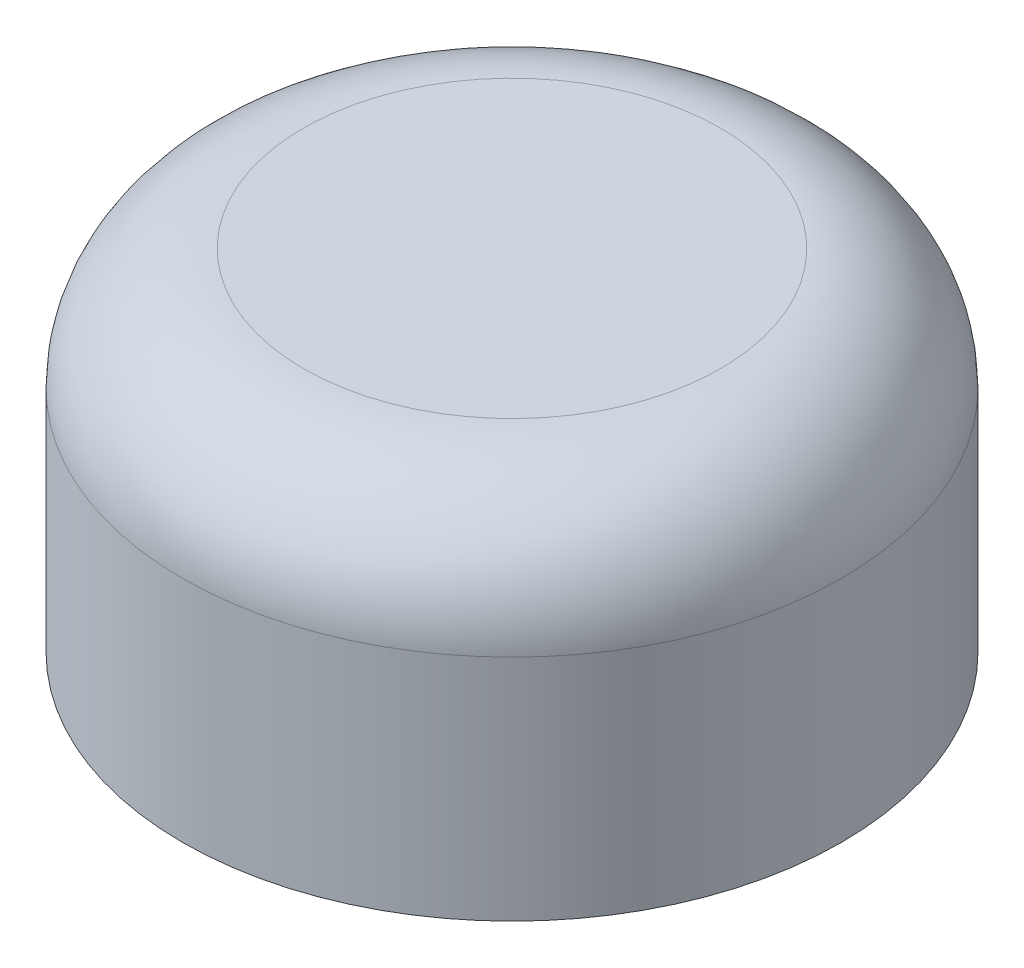
SolidWorks part; units mm, degrees
material "PW30:30:Sc:0:"
ref_plane "Front" through (0, 0, 0) normal (0, 0, 1) x (1, 0, 0)
ref_plane "Top" through (0, 0, 0) normal (0, 1, 0) x (1, 0, 0)
ref_plane "Right" through (0, 0, 0) normal (1, 0, 0) x (0, 0, -1)
sketch "Sketch1" plane through (0, 0, 0) normal (0, 0, 1) x (1, 0, 0)
  line L0 (0, 0) -> (0, 28.1396) construction
  line L1 (0, 22.6983) -> (12.446, 22.6983)
  line L2 (12.446, 22.6983) -> (12.446, 9.4903)
  line L3 (12.446, 9.4903) -> (10.16, 9.4903)
  line L5 (10.16, 9.4903) -> (10.16, 10.7603)
  line L6 (10.16, 10.7603) -> (11.684, 10.7603)
  line L7 (11.684, 10.7603) -> (11.684, 21.4283)
  line L8 (11.684, 21.4283) -> (0, 21.4283)
  line L9 (0, 21.4283) -> (0, 22.6983)
  dimension "D1" = 1.27
  dimension "D2" = 12.446
  dimension "D3" = 0.762
  dimension "D4" = 1.27
  dimension "D5" = 2.286
  dimension "D6" = 13.208
revolve "Base-Revolve" add sketch "Sketch1" angle 360 about L0
fillet "Fillet1" radius 3.81 1 edges at (0, 21.4283, -11.684)
fillet "Fillet2" radius 4.572 1 edges at (0, 22.6983, -12.446)
